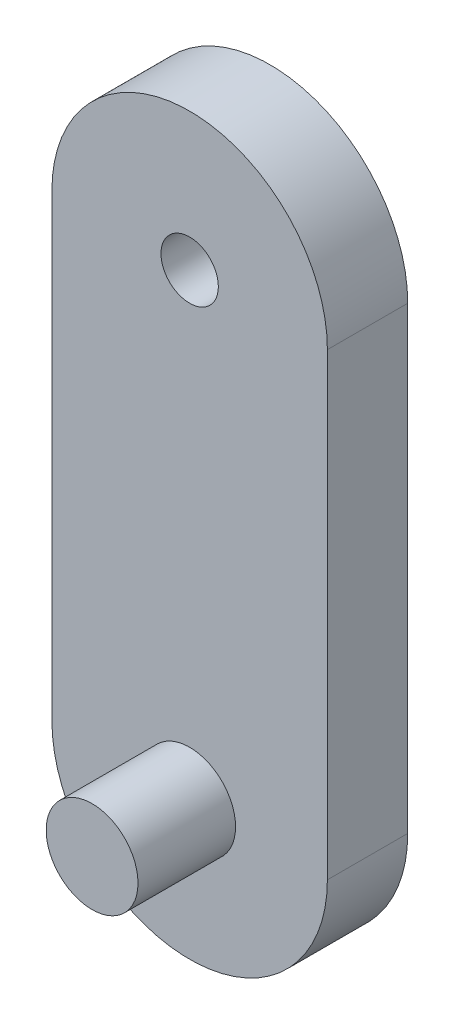
SolidWorks part; units mm, degrees
ref_plane "Front Plane" through (0, 0, 0) normal (0, 0, 1) x (1, 0, 0)
ref_plane "Top Plane" through (0, 0, 0) normal (0, 1, 0) x (1, 0, 0)
ref_plane "Right Plane" through (0, 0, 0) normal (1, 0, 0) x (0, 0, -1)
sketch "Sketch1" plane through (0, 0, 0) normal (0, 0, 1) x (1, 0, 0)
  line L2 (0, 0) -> (0, 40)
  line L4 (-24, 0) -> (-24, 40)
  arc A0 (-24, 0) -> (0, 0) centre (-12, 0) ccw
  arc A1 (-24, 40) -> (0, 40) centre (-12, 40) cw
  dimension "D1" = 24
  dimension "D2" = 40
extrude "Boss-Extrude1" add sketch "Sketch1" along normal blind 7
sketch "Sketch2" plane through (0, 0, 7) normal (0, 0, 1) x (1, 0, 0)
  circle A0 centre (-12, 0) radius 4
  dimension "D1" = 8
extrude "Boss-Extrude2" add sketch "Sketch2" along normal blind 8.5
sketch "Sketch3" plane through (0, 0, 7) normal (0, 0, 1) x (1, 0, 0)
  circle A0 centre (-12, 40) radius 2.5
  dimension "D1" = 5
extrude "Cut-Extrude1" cut sketch "Sketch3" against normal blind 10.5
